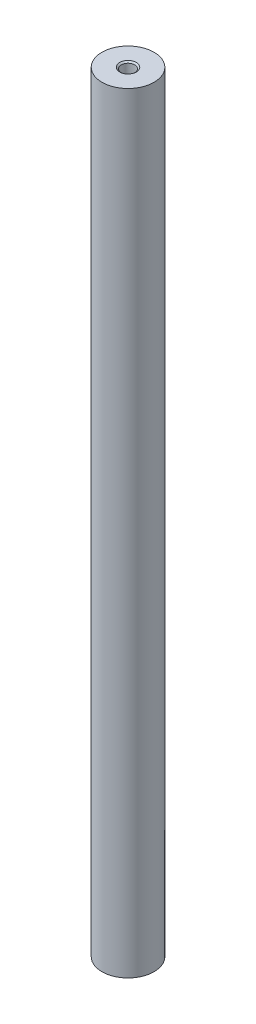
SolidWorks part; units mm, degrees
material "6061 Alloy"
ref_plane "Front" through (0, 0, 0) normal (0, 0, 1) x (1, 0, 0)
ref_plane "Top" through (0, 0, 0) normal (0, 1, 0) x (1, 0, 0)
ref_plane "Right" through (0, 0, 0) normal (1, 0, 0) x (0, 0, -1)
sketch "Sketch1" plane through (0, 0, 0) normal (0, 1, 0) x (1, 0, 0)
  circle A0 centre (0, 0) radius 6.35
  dimension "D1" = 12.7
extrude "Boss-Extrude1" add sketch "Sketch1" along normal blind 187.8203
hole_wizard "1/4-20 Tapped Hole1" positions "Sketch2" profile "Sketch4" tap size "1/4-20" standard "ANSI Inch"
sketch "Sketch2" plane through (0, 0, 0) normal (0, -1, 0) x (-1, 0, 0)
  point P0 (0, 0)
sketch "Sketch4" plane through (0, 0, 0) normal (1, 0, 0) x (0, 0, -1)
  line L0 (0, 0) -> (0, 23.1238)
  line L1 (0, 23.1238) -> (2.5527, 21.59)
  line L2 (2.5527, 21.59) -> (2.5527, 1.055)
  line L3 (2.5527, 1.055) -> (3.81, 0)
  line L5 (3.81, 0) -> (0, 0)
  line L6 (-2.5527, 1.055) -> (-3.81, 0) construction
  line L10 (0, 23.1238) -> (-2.5527, 21.59) construction
  line L11 (0, -6.35) -> (0, 107.95) construction
  dimension "Tap Drill Dia." = 5.1054
  dimension "Tap Drill Depth" = 21.59
  dimension "Near C'Sink Dia." = 7.62
  dimension "Near C'Sink Angle" = 100
  dimension "Drill Angle" = 118
cosmetic thread "Hole Thread1" parameters "D1"=17.78, "D2"=6.35
hole_wizard "M4x0.7 Tapped Hole1" positions "Sketch5" profile "Sketch6" tap size "M4x0.7" standard "ANSI Metric"
sketch "Sketch5" plane through (0, 187.8203, 0) normal (0, 1, 0) x (1, 0, 0)
  point P0 (0, 0)
sketch "Sketch6" plane through (0, 187.8203, 0) normal (1, 0, 0) x (0, 0, 1)
  line L0 (0, 0) -> (0, 18.7206)
  line L1 (0, 18.7206) -> (1.65, 17.7292)
  line L2 (1.65, 17.7292) -> (1.65, 0.3147)
  line L3 (1.65, 0.3147) -> (2.025, 0)
  line L5 (2.025, 0) -> (0, 0)
  line L6 (-1.65, 0.3147) -> (-2.025, 0) construction
  line L10 (0, 18.7206) -> (-1.65, 17.7292) construction
  line L11 (0, -6.35) -> (0, 107.95) construction
  dimension "Tap Drill Dia." = 3.3
  dimension "Tap Drill Depth" = 17.7292
  dimension "Near C'Sink Dia." = 4.05
  dimension "Near C'Sink Angle" = 100
  dimension "Drill Angle" = 118
cosmetic thread "Hole Thread2" parameters "D1"=15.621, "D2"=4
